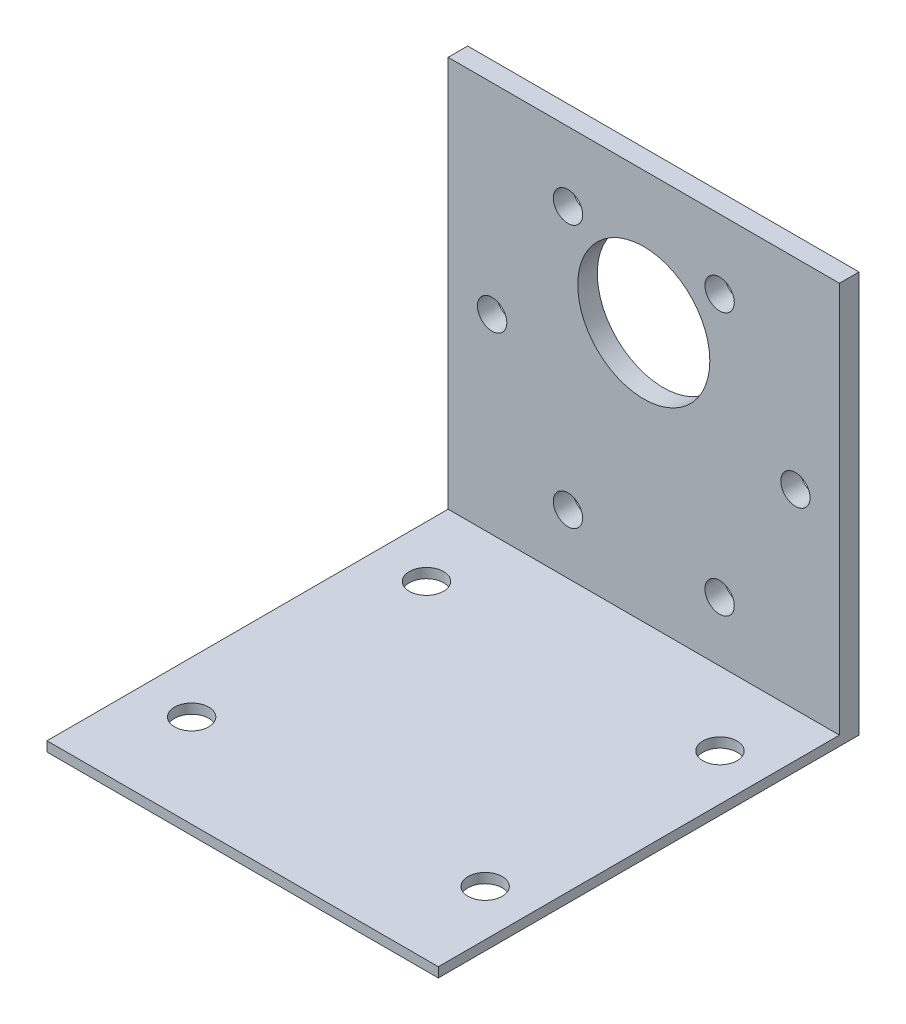
SolidWorks part; units mm, degrees
ref_plane "Front Plane" through (0, 0, 0) normal (0, 0, 1) x (1, 0, 0)
ref_plane "Top Plane" through (0, 0, 0) normal (0, 1, 0) x (1, 0, 0)
ref_plane "Right Plane" through (0, 0, 0) normal (1, 0, 0) x (0, 0, -1)
sketch "Sketch1" plane through (0, 0, 0) normal (0, 1, 0) x (1, 0, 0)
  line L0 (-20, 19.5) -> (20, 19.5)
  line L1 (-20, -21.5) -> (20, -21.5)
  line L2 (-20, -21.5) -> (-20, 21.5)
  line L3 (-20, 21.5) -> (20, 21.5)
  line L4 (20, -21.5) -> (20, 21.5)
  line L5 (-20, -21.5) -> (20, 21.5) construction
  line L6 (-20, 21.5) -> (20, -21.5) construction
  circle A7 centre (-14.7151, 12) radius 1.75
  circle A8 centre (15.2849, 12) radius 1.75
  circle A9 centre (-14.7151, -12) radius 1.75
  circle A10 centre (15.2849, -12) radius 1.75
  point P0 (0, 0)
  dimension "D4" = 30
  dimension "D5" = 3.5
  dimension "D6" = 3.5
  dimension "D7" = 24
  dimension "D8" = 9.5
  dimension "D10" = 3.5
  dimension "D12" = 3.5
  dimension "D1" = 2
  dimension "D2" = 40
  dimension "D3" = 43
extrude "Boss-Extrude1" add sketch "Sketch1" against normal blind 1
sketch "Sketch4" plane through (0, 0, 0) normal (0, 1, 0) x (1, 0, 0)
  line L1 (-20, -21.5) -> (-20, 21.5) construction
  line L2 (20, -21.5) -> (20, 21.5) construction
  line L5 (-20, 21.5) -> (20, 21.5)
  line L6 (-20, 21.5) -> (-20, 19.5)
  line L7 (-20, 19.5) -> (20, 19.5)
  line L8 (-20, -21.5) -> (20, -21.5)
  line L9 (20, -21.5) -> (20, 21.5)
  line L10 (20, 21.5) -> (-20, 21.5)
  line L11 (-20, 21.5) -> (-20, -21.5)
  line L12 (-20, -21.5) -> (20, -21.5)
  line L13 (20, -21.5) -> (20, 12.2)
  line L15 (-20, 12.2) -> (-20, -21.5)
  line L16 (20, 21.5) -> (20, 19.5)
  line M13 (20, -21.5) -> (20, 21.5)
  line M14 (20, 21.5) -> (-20, 21.5)
  line M15 (-20, 21.5) -> (-20, -21.5)
  dimension "D1" = 2
  dimension "D2" = 0
extrude "Boss-Extrude2" add sketch "Sketch4" along normal blind 40 contours L7 M15 M13 M14
sketch "Sketch5" plane through (0, 0, -19.5) normal (0, 0, 1) x (1, 0, 0)
  line L0 (-20, 40) -> (20, -1) construction
  line L1 (-20, -1) -> (20, 40) construction
  line L2 (0, 19.5) -> (0, 4) construction
  line L3 (0, 19.5) -> (0, 26.5) construction
  circle A11 centre (0, 26.5) radius 6.75
  point P18 (0, 19.5)
  point P28 (0, 19.5)
  dimension "D2" = 7
  dimension "D5" = 15.5
  dimension "D6" = 13.5
extrude "Cut-Extrude5" cut sketch "Sketch5" against normal blind 34
sketch "Sketch8" plane through (0, 0, -19.5) normal (0, 0, 1) x (1, 0, 0)
  line L0 (-20, 40) -> (20, -1) construction
  line L1 (20, 40) -> (-20, -1) construction
  line L2 (0, 19.5) -> (0, 4) construction
  line L3 (-20, 19.5) -> (20, 19.5) construction
  line L4 (-20, 40) -> (-20, 0) construction
  line L5 (20, 40) -> (20, 0) construction
  line L6 (15.5, 19.5) -> (-15.5, 19.5)
  circle A0 centre (0, 4) radius 1.5
  circle A1 centre (-15.5, 19.5) radius 1.5
  circle A3 centre (0, 19.5) radius 15.5
  circle A4 centre (-7.75, 32.9234) radius 1.5
  circle A5 centre (7.75, 32.9234) radius 1.5
  circle A6 centre (15.5, 19.5) radius 1.5
  circle A7 centre (7.75, 6.0766) radius 1.5
  circle A8 centre (-7.75, 6.0766) radius 1.5
  point P21 (0, 19.5)
  point P35 (0, 19.5)
  dimension "D2" = 3
  dimension "D4" = 3
  dimension "D5" = 6
  dimension "D1" = 15.5
  dimension "D3" = 31
extrude "Cut-Extrude6" cut sketch "Sketch8" against normal blind 10 contours A7 | A6 | A5 | A4 | A1 | A8
